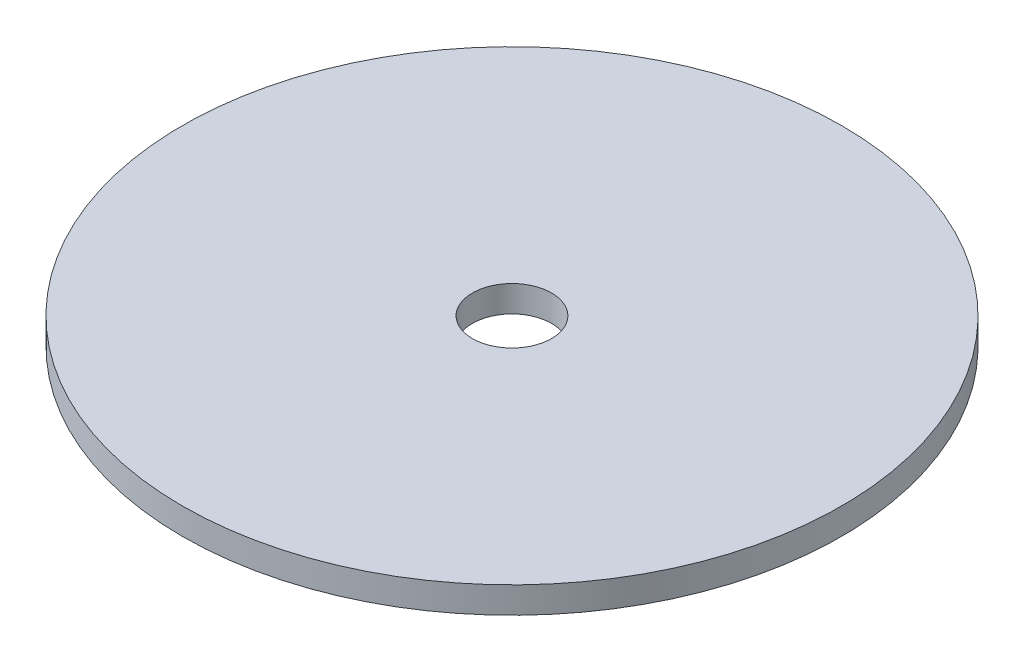
SolidWorks part; units mm, degrees
material "Wrought Stainless Steel"
ref_plane "Front Plane" through (0, 0, 0) normal (0, 0, 1) x (1, 0, 0)
ref_plane "Top Plane" through (0, 0, 0) normal (0, 1, 0) x (1, 0, 0)
ref_plane "Right Plane" through (0, 0, 0) normal (1, 0, 0) x (0, 0, -1)
sketch "Sketch1" plane through (0, 0, 0) normal (0, 1, 0) x (1, 0, 0)
  circle A0 centre (0, 0) radius 12.5
  circle A1 centre (0, 0) radius 1.5
extrude "Boss-Extrude1" add sketch "Sketch1" along normal blind 1
